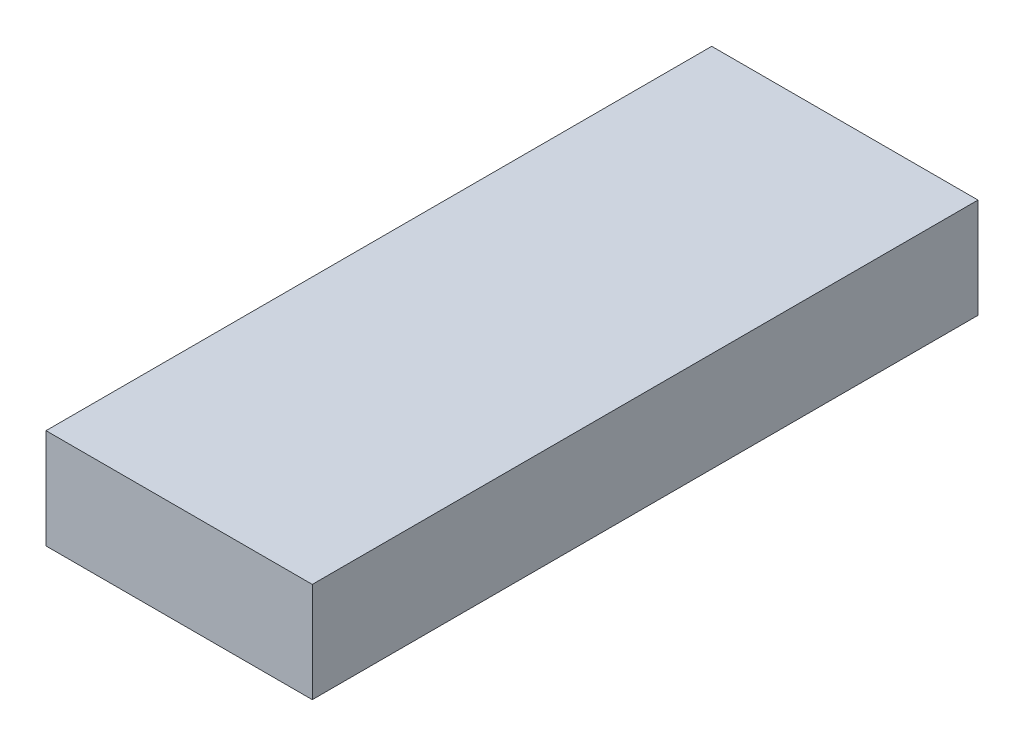
SolidWorks part; units mm, degrees
ref_plane "Front Plane" through (0, 0, 0) normal (0, 0, 1) x (1, 0, 0)
ref_plane "Top Plane" through (0, 0, 0) normal (0, 1, 0) x (1, 0, 0)
ref_plane "Right Plane" through (0, 0, 0) normal (1, 0, 0) x (0, 0, -1)
sketch "Sketch1" plane through (0, 0, 0) normal (0, 0, 1) x (1, 0, 0)
  line L1 (0, 0) -> (-20.32, 0)
  line L2 (0, 0) -> (0, 7.62)
  line L3 (0, 7.62) -> (-20.32, 7.62)
  line L4 (-20.32, 0) -> (-20.32, 7.62)
  dimension "D1" = 7.62
  dimension "D2" = 20.32
extrude "Boss-Extrude1" add sketch "Sketch1" along normal blind 50.8
